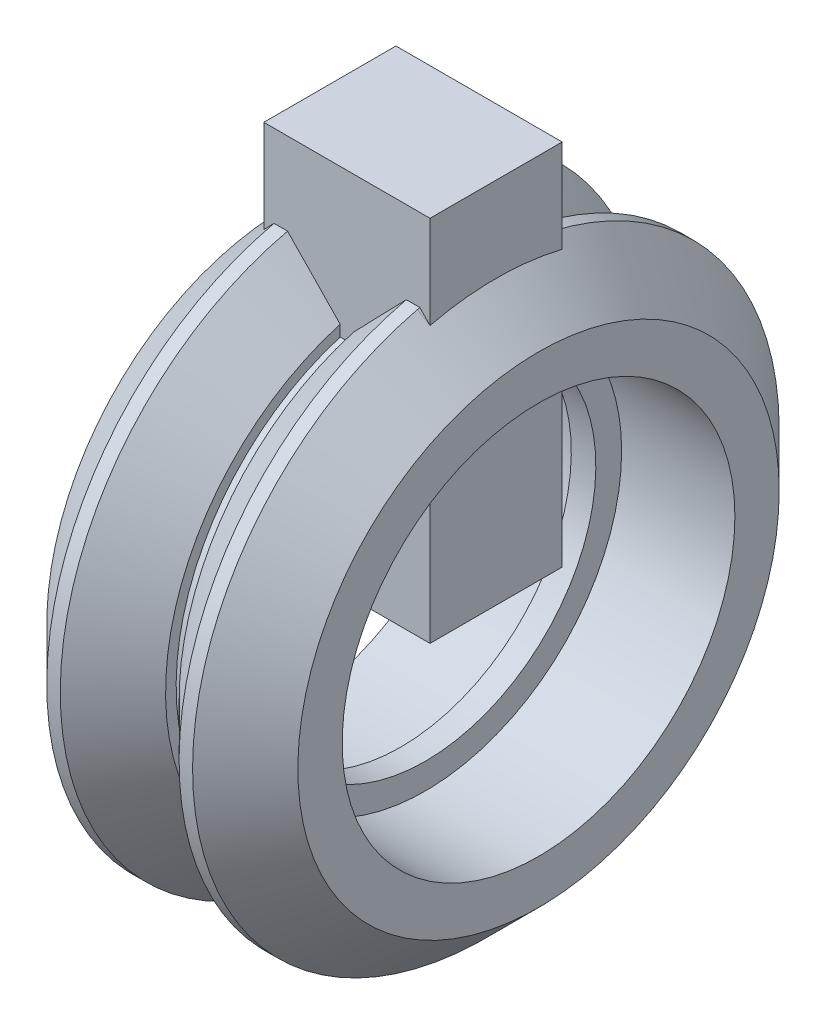
SolidWorks part; units mm, degrees
material "Chrome Stainless Steel"
ref_plane "Front Plane" through (0, 0, 0) normal (0, 0, 1) x (1, 0, 0)
ref_plane "Top Plane" through (0, 0, 0) normal (0, 1, 0) x (1, 0, 0)
ref_plane "Right Plane" through (0, 0, 0) normal (1, 0, 0) x (0, 0, -1)
sketch "Sketch1" plane through (0, 0, 0) normal (0, 0, 1) x (1, 0, 0)
  line L0 (0.5, 6.95) -> (-0.5, 6.95)
  line L1 (-0.5, 6.95) -> (-0.5, 8)
  line L2 (-0.5, 8) -> (-5.115, 8)
  line L3 (-5.115, 8) -> (-5.115, 9.805)
  line L4 (-5.115, 9.805) -> (-2.97, 11.95)
  line L5 (-2.97, 11.95) -> (-2.42, 11.95)
  line L6 (0, 12) -> (0, 6.95) construction
  line L7 (5.115, 9.805) -> (2.97, 11.95)
  line L8 (5.115, 8) -> (5.115, 9.805)
  line L9 (0.5, 8) -> (5.115, 8)
  line L10 (0.5, 6.95) -> (0.5, 8)
  line L11 (0, 0) -> (-12.6359, 0) construction
  line L12 (-2.42, 11.95) -> (-0.275, 9.805)
  line L13 (-0.275, 9.805) -> (-0.275, 9.375)
  line L14 (-0.275, 9.375) -> (0.275, 9.375)
  line L15 (0.275, 9.805) -> (0.275, 9.375)
  line L16 (2.97, 11.95) -> (2.42, 11.95)
  line L17 (2.42, 11.95) -> (0.275, 9.805)
  point P20 (0, 9.375)
  dimension "D1" = 0.55
  dimension "D2" = 16
  dimension "D3" = 23.9
  dimension "D4" = 1
  dimension "D5" = 45
  dimension "D6" = 10.23
  dimension "D7" = 18.75
  dimension "D8" = 13.9
revolve "Revolve1" add sketch "Sketch1" angle 360 about L11
sketch "Sketch2" plane through (0, 0, 0) normal (0, 1, 0) x (1, 0, 0)
  line L1 (3.3862, -2.6919) -> (-3.3862, -2.6919)
  line L2 (3.3862, -2.6919) -> (3.3862, 2.6919)
  line L3 (3.3862, 2.6919) -> (-3.3862, 2.6919)
  line L4 (-3.3862, -2.6919) -> (-3.3862, 2.6919)
  line L5 (3.3862, -2.6919) -> (-3.3862, 2.6919) construction
  line L6 (3.3862, 2.6919) -> (-3.3862, -2.6919) construction
  point P0 (0, 0)
extrude "Boss-Extrude1" add sketch "Sketch2" along normal blind 15
